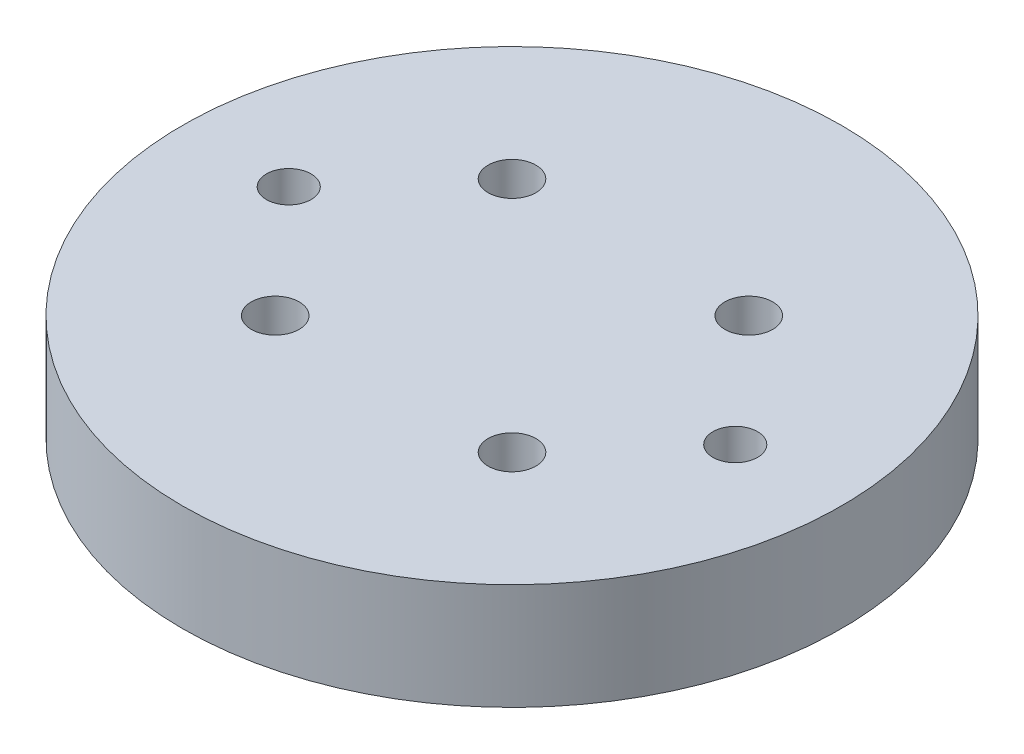
SolidWorks part; units mm, degrees
ref_plane "Front" through (0, 0, 0) normal (0, 0, 1) x (1, 0, 0)
ref_plane "Top" through (0, 0, 0) normal (0, 1, 0) x (1, 0, 0)
ref_plane "Right" through (0, 0, 0) normal (1, 0, 0) x (0, 0, -1)
sketch "草图1" plane through (0, 0, 0) normal (0, 1, 0) x (1, 0, 0)
  circle A0 centre (0, 0) radius 31
  dimension "D1" = 62
extrude "凸台-拉伸1" add sketch "草图1" along normal blind 10
sketch "草图2" plane through (0, 10, 0) normal (0, 1, 0) x (1, 0, 0)
  line L0 (-38.0299, 0) -> (41.4465, 0) construction
  line L1 (0, 35.6023) -> (0, -38.8213) construction
  point P5 (-21, 0)
  point P11 (21, 0)
  dimension "D1" = 21
hole_wizard "M5 螺纹孔2" positions "3D草图1" profile "草图3" tap size "M5" standard "GB" end condition through all
sketch3d "3D草图1"
  point P0 (-21, 10, 0)
  point P3 (21, 10, 0)
sketch "草图3" plane through (-21, 10, 0) normal (1, 0, 0) x (0, 0, 1)
  line L0 (0, 0) -> (0, 10)
  line L1 (0, 10) -> (2.1, 10)
  line L2 (2.1, 10) -> (2.1, 0)
  line L5 (2.1, 0) -> (0, 0)
  line L11 (0, -6.35) -> (0, 107.95) construction
  dimension "通孔螺纹孔钻头直径" = 4.2
  dimension "通孔螺纹孔钻头深度" = 10
cosmetic thread "孔螺蚊线1"
cosmetic thread "孔螺蚊线2"
sketch "草图4" plane through (0, 0, 0) normal (0, -1, 0) x (1, 0, 0)
  line L0 (-40.506, 0) -> (45.3789, 0) construction
  line L1 (0, 38.1653) -> (0, -39.9404) construction
  line L2 (0, 0) -> (-16.0297, 16.0297) construction
  circle A0 centre (0, 0) radius 15.75 construction
  point P7 (-11.1369, 11.1369)
  point P12 (11.1369, 11.1369)
  point P13 (11.1369, -11.1369)
  point P14 (-11.1369, -11.1369)
  point P15 (0, 0)
  dimension "D1" = 31.5
  dimension "D2" = 45
  dimension "D3" = 4
hole_wizard "打孔尺寸(%根据)内六角圆柱头螺钉的类型2" positions "3D草图2" profile "草图5" counterbore size "M4" standard "GB" end condition through all
sketch3d "3D草图2"
  point P0 (-11.1369, 0, 11.1369)
  point P3 (11.1369, 0, 11.1369)
  point P6 (11.1369, 0, -11.1369)
  point P9 (-11.1369, 0, -11.1369)
sketch "草图5" plane through (-11.1369, 0, 11.1369) normal (1, 0, 0) x (0, 0, -1)
  line L0 (0, 0) -> (0, 10)
  line L1 (0, 10) -> (2.25, 10)
  line L3 (2.25, 10) -> (2.25, 4.6)
  line L4 (2.25, 4.6) -> (4, 4.6)
  line L5 (4, 4.6) -> (4, 0)
  line L7 (4, 0) -> (0, 0)
  line L11 (0, -6.35) -> (0, 107.95) construction
  dimension "通孔孔直径" = 4.5
  dimension "通孔孔深度" = 10
  dimension "柱形沉头孔直径" = 8
  dimension "柱形沉头孔深度" = 4.6
sketch "草图6" plane through (0, 10, 0) normal (0, 1, 0) x (1, 0, 0)
  circle A0 centre (0, 0) radius 15.75 construction
  dimension "D1" = 31.5
